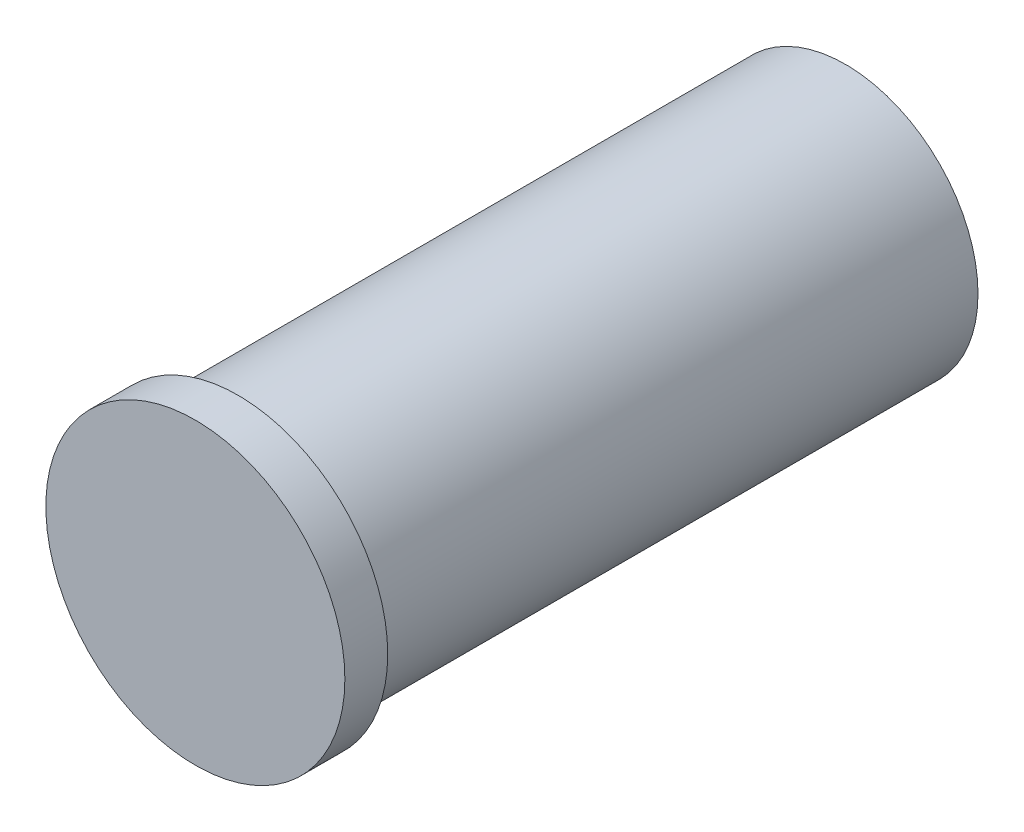
SolidWorks part; units mm, degrees
ref_plane "Front Plane" through (0, 0, 0) normal (0, 0, 1) x (1, 0, 0)
ref_plane "Top Plane" through (0, 0, 0) normal (0, 1, 0) x (1, 0, 0)
ref_plane "Right Plane" through (0, 0, 0) normal (1, 0, 0) x (0, 0, -1)
sketch "Sketch1" plane through (0, 0, 0) normal (0, 0, 1) x (1, 0, 0)
  circle A0 centre (0, 0) radius 3.925
  dimension "D1" = 7.85
extrude "Boss-Extrude1" add sketch "Sketch1" along normal blind 18
sketch "Sketch2" plane through (0, 0, 18) normal (0, 0, 1) x (1, 0, 0)
  circle A0 centre (0, 0) radius 4.4311
extrude "Boss-Extrude2" add sketch "Sketch2" along normal blind 1.27
